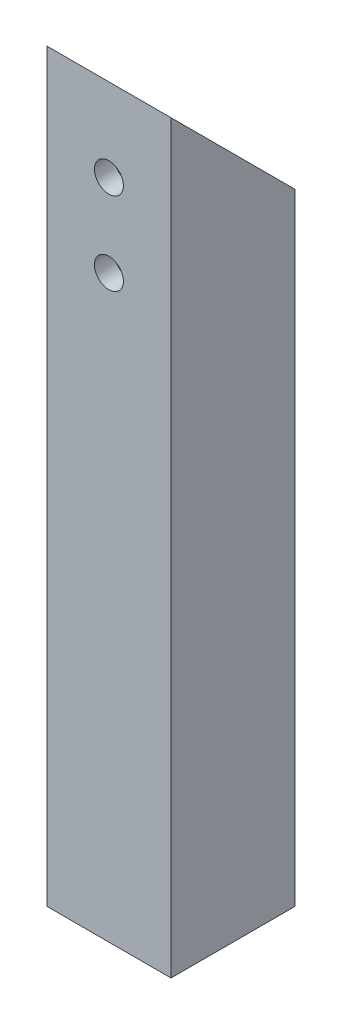
SolidWorks part; units mm, degrees
ref_plane "Front Plane" through (0, 0, 0) normal (0, 0, 1) x (1, 0, 0)
ref_plane "Top Plane" through (0, 0, 0) normal (0, 1, 0) x (1, 0, 0)
ref_plane "Right Plane" through (0, 0, 0) normal (1, 0, 0) x (0, 0, -1)
sketch "Sketch1" plane through (0, 0, 0) normal (0, 1, 0) x (1, 0, 0)
  line L1 (-7.5, 7.5) -> (7.5, 7.5)
  line L2 (-7.5, 7.5) -> (-7.5, -7.5)
  line L3 (-7.5, -7.5) -> (7.5, -7.5)
  line L4 (7.5, 7.5) -> (7.5, -7.5)
  line L5 (-7.5, 7.5) -> (7.5, -7.5) construction
  line L6 (-7.5, -7.5) -> (7.5, 7.5) construction
  circle A0 centre (0, 0) radius 2.5
  point P0 (0, 0)
  dimension "D2" = 5
  dimension "D1" = 15
extrude "Boss-Extrude1" add sketch "Sketch1" against normal blind 90
sketch "Sketch2" plane through (0, 0, 0) normal (0, 1, 0) x (1, 0, 0)
  line L0 (7.5, 7.5) -> (-7.5, 7.5) construction
  line L1 (-5.087, 5.087) -> (5.087, 5.087)
  line L2 (-5.087, 5.087) -> (-5.087, -5.087)
  line L3 (-5.087, -5.087) -> (5.087, -5.087)
  line L4 (5.087, 5.087) -> (5.087, -5.087)
  line L5 (-5.087, 5.087) -> (5.087, -5.087) construction
  line L6 (-5.087, -5.087) -> (5.087, 5.087) construction
  point P0 (0, 0)
  dimension "D1" = 2.413
extrude "Cut-Extrude1" cut sketch "Sketch2" against normal blind 83
sketch "Sketch3" plane through (0, 0, 0) normal (1, 0, 0) x (0, 0, -1)
  line L0 (-7.5, 0) -> (7.5, -15)
  line L1 (7.5, -90) -> (7.5, 0) construction
  line L2 (7.5, -15) -> (7.5, 0)
  line L3 (7.5, 0) -> (-7.5, 0)
  dimension "D1" = 45
extrude "Cut-Extrude2" cut sketch "Sketch3" against normal blind 83 and the other way blind 83
sketch "Sketch4" plane through (0, 0, 0) normal (0, 0, 1) x (1, 0, 0)
  line L0 (0, -10) -> (0, -20) construction
  line L4 (0, 0) -> (0, -10) construction
  circle A1 centre (0, -10) radius 1.75
  circle A2 centre (0, -20) radius 1.75
  dimension "D2" = 3.5
  dimension "D3" = 10
  dimension "D1" = 10
extrude "Cut-Extrude3" cut sketch "Sketch4" along normal blind 83
